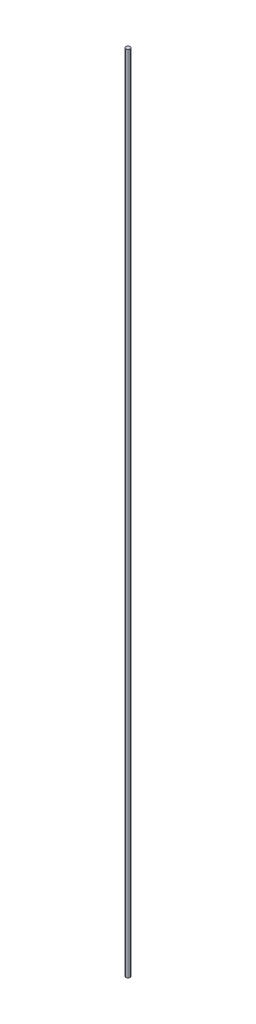
SolidWorks part; units mm, degrees
ref_plane "Front Plane" through (0, 0, 0) normal (0, 0, 1) x (1, 0, 0)
ref_plane "Top Plane" through (0, 0, 0) normal (0, 1, 0) x (1, 0, 0)
ref_plane "Right Plane" through (0, 0, 0) normal (1, 0, 0) x (0, 0, -1)
sketch "Sketch1" plane through (0, 0, 0) normal (0, 0, 1) x (1, 0, 0)
  line L0 (0, 0) -> (0, 2457.196)
  dimension "Length from Tank Model" = 2457.196
sweep "Sweep1" add path "Sketch1" circular profile diameter 12.7 parameters "D3"=12.7
equation "\"rebar diameter\"= .5"
equation "\"D3@Sweep1\"=\"rebar diameter\""
